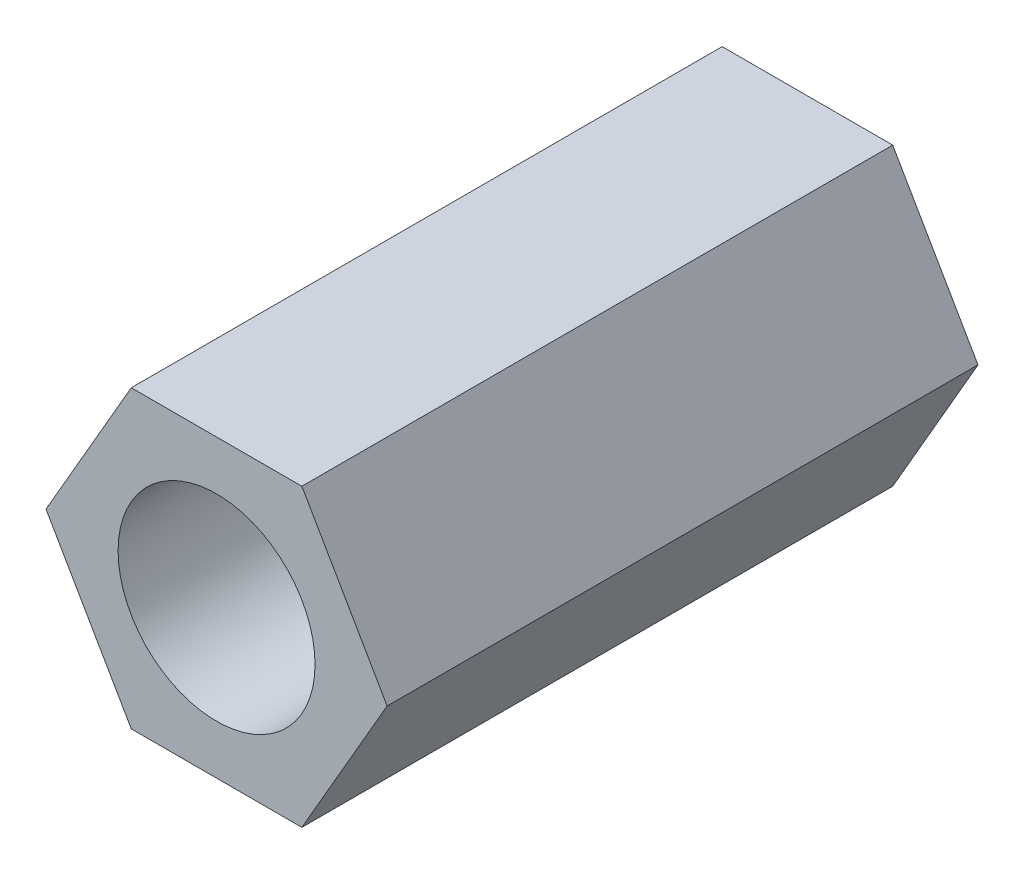
SolidWorks part; units mm, degrees
material "Zinc AC41A Alloy, As Cast"
ref_plane "Front Plane" through (0, 0, 0) normal (0, 0, 1) x (1, 0, 0)
ref_plane "Top Plane" through (0, 0, 0) normal (0, 1, 0) x (1, 0, 0)
ref_plane "Right Plane" through (0, 0, 0) normal (1, 0, 0) x (0, 0, -1)
sketch "Sketch1" plane through (0, 0, 0) normal (0, 0, 1) x (1, 0, 0)
  line L1 (-10.9985, 0) -> (-5.4993, -9.525)
  line L2 (-5.4993, -9.525) -> (5.4993, -9.525)
  line L3 (5.4993, -9.525) -> (10.9985, 0)
  line L4 (10.9985, 0) -> (5.4993, 9.525)
  line L5 (5.4993, 9.525) -> (-5.4993, 9.525)
  line L6 (-5.4993, 9.525) -> (-10.9985, 0)
  circle A0 centre (0, 0) radius 9.525 construction
  dimension "D1" = 19.05
extrude "Boss-Extrude1" add sketch "Sketch1" along normal blind 38.1
sketch "Sketch2" plane through (0, 0, 38.1) normal (0, 0, 1) x (1, 0, 0)
  circle A0 centre (0, 0) radius 6.35
  dimension "D1" = 12.7
extrude "Cut-Extrude1" cut sketch "Sketch2" against normal through all
